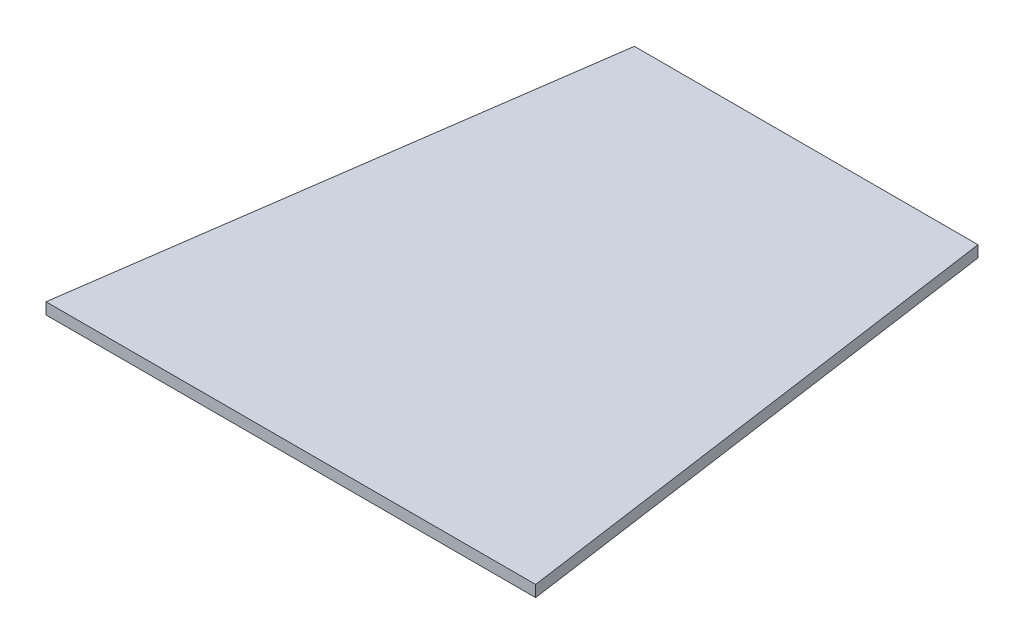
SolidWorks part; units mm, degrees
ref_plane "前视基准面" through (0, 0, 0) normal (0, 0, 1) x (1, 0, 0)
ref_plane "上视基准面" through (0, 0, 0) normal (0, 1, 0) x (1, 0, 0)
ref_plane "右视基准面" through (0, 0, 0) normal (1, 0, 0) x (0, 0, -1)
other "Configuration Table"
sketch "草图1" plane through (0, 0, 0) normal (0, 1, 0) x (1, 0, 0)
  line L0 (0, 0) -> (0, 90) construction
  line L1 (30, 90) -> (-30, 90)
  line L2 (-30, 90) -> (-42.75, 0)
  line L3 (-42.75, 0) -> (42.75, 0)
  line L4 (30, 90) -> (42.75, 0)
  dimension "D1" = 42.75
  dimension "D2" = 90
  dimension "D3" = 30
extrude "凸台-拉伸1" add sketch "草图1" along normal blind 2
